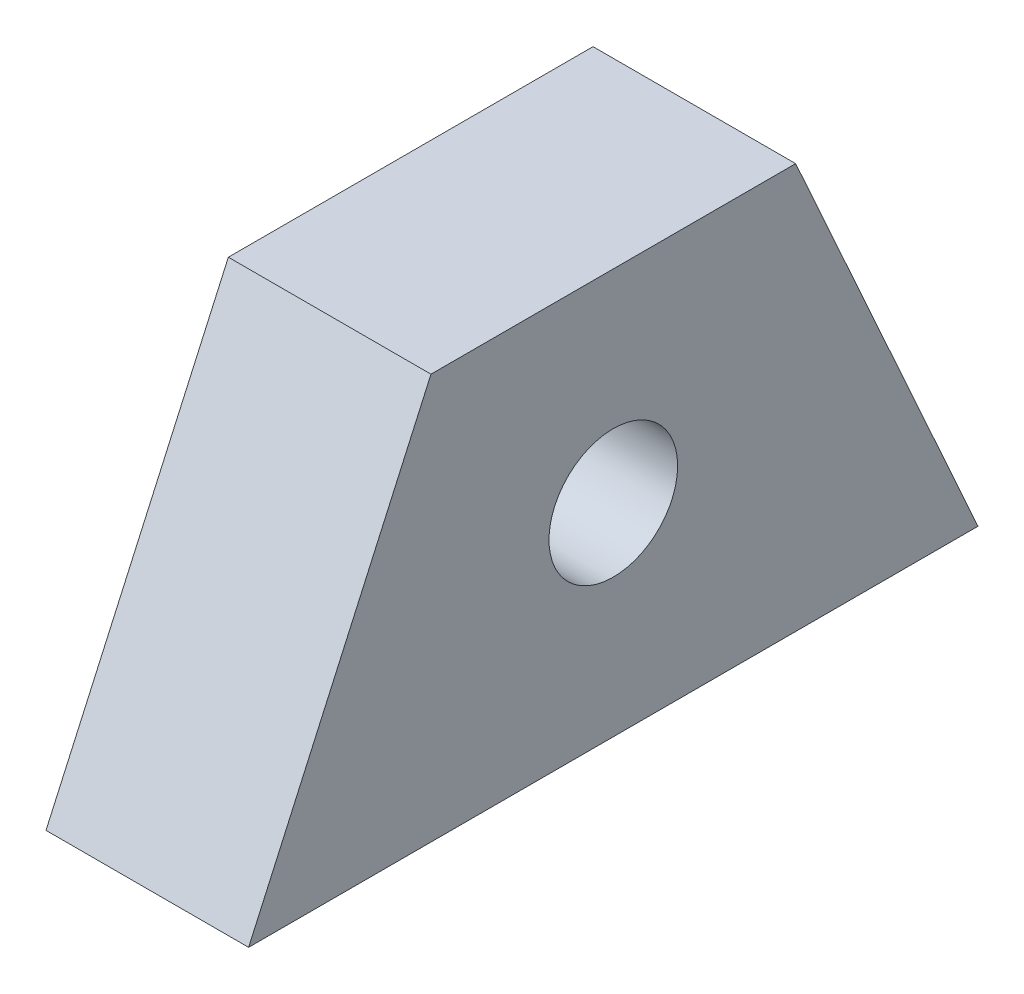
SolidWorks part; units mm, degrees
ref_plane "Front Plane" through (0, 0, 0) normal (0, 0, 1) x (1, 0, 0)
ref_plane "Top Plane" through (0, 0, 0) normal (0, 1, 0) x (1, 0, 0)
ref_plane "Right Plane" through (0, 0, 0) normal (1, 0, 0) x (0, 0, -1)
sketch "Sketch1" plane through (0, 0, 0) normal (1, 0, 0) x (0, 0, -1)
  line L0 (0, 0) -> (18, 0)
  line L1 (55, 0) -> (-55, 0) construction
  line L2 (18, 0) -> (9, 20)
  line L3 (9, 20) -> (-9, 20)
  line L4 (0, 55) -> (0, -55) construction
  line L5 (0, 20) -> (0, 0)
  line L6 (0, 0) -> (-18, 0)
  line L7 (-18, 0) -> (-9, 20)
  circle A0 centre (0, 10) radius 3.175
  point P5 (9, 0)
  point P12 (-9, 0)
extrude "Boss-Extrude1" add sketch "Sketch1" along normal blind 10 contours A0 L5 L0 L2 L3 | A0 L5 L3 L7 L6
